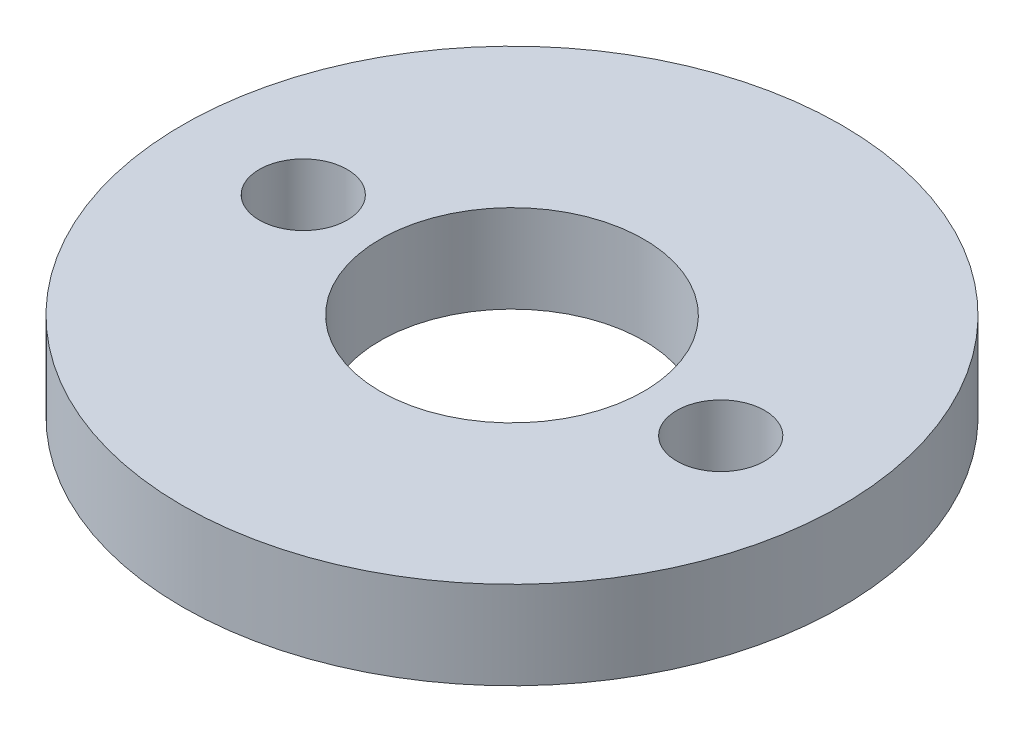
SolidWorks part; units mm, degrees
ref_plane "Front Plane" through (0, 0, 0) normal (0, 0, 1) x (1, 0, 0)
ref_plane "Top Plane" through (0, 0, 0) normal (0, 1, 0) x (1, 0, 0)
ref_plane "Right Plane" through (0, 0, 0) normal (1, 0, 0) x (0, 0, -1)
sketch "Sketch1" plane through (0, 0, 0) normal (0, 1, 0) x (1, 0, 0)
  circle A0 centre (0, 0) radius 15
extrude "Boss-Extrude1" add sketch "Sketch1" along normal blind 4
sketch "Sketch2" plane through (0, 4, 0) normal (0, 1, 0) x (1, 0, 0)
  circle A0 centre (0, 0) radius 6
extrude "Cut-Extrude1" cut sketch "Sketch2" against normal through all
sketch "Sketch3" plane through (0, 4, 0) normal (0, 1, 0) x (1, 0, 0)
  line L0 (0, 0) -> (-17.0573, 0) construction
  line L1 (0, 16.1478) -> (0, 0) construction
  circle A0 centre (-9.5, 0) radius 2
  circle A1 centre (9.5, 0) radius 2
  dimension "D1" = 9.5
extrude "Cut-Extrude2" cut sketch "Sketch3" against normal through all
